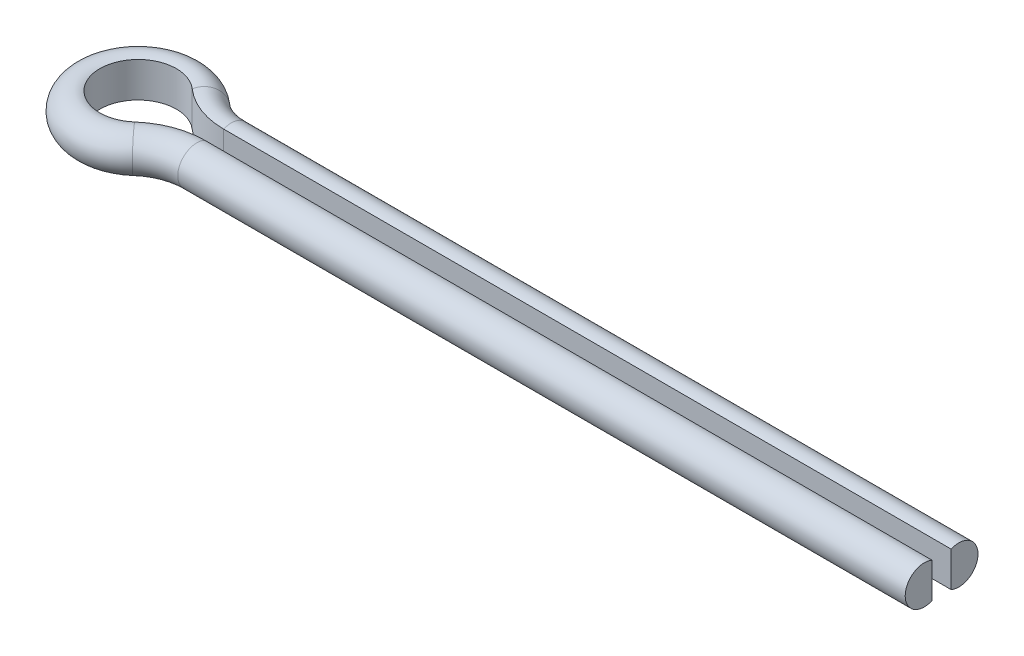
SolidWorks part; units mm, degrees
ref_plane "Front Plane" through (0, 0, 0) normal (0, 0, 1) x (1, 0, 0)
ref_plane "Top Plane" through (0, 0, 0) normal (0, 1, 0) x (1, 0, 0)
ref_plane "Right Plane" through (0, 0, 0) normal (1, 0, 0) x (0, 0, -1)
sketch "Sketch2" plane through (0, 0, 0) normal (0, 1, 0) x (1, 0, 0)
  line L0 (0, 0) -> (53.9373, 0) construction
  line L1 (104.8412, 1.25) -> (9.9216, 1.25)
  line L2 (104.8412, -1.25) -> (9.9216, -1.25)
  arc A0 (3.3072, 3.75) -> (3.3072, -3.75) centre (0, 0) ccw
  arc A1 (9.9216, -1.25) -> (3.3072, -3.75) centre (9.9216, -11.25) ccw
  arc A2 (9.9216, 1.25) -> (3.3072, 3.75) centre (9.9216, 11.25) cw
  point P9 (4.8412, -1.25)
  point P12 (4.8412, 1.25)
  dimension "D1" = 10
  dimension "D4" = 10
  dimension "D2" = 1.25
  dimension "D3" = 100
ref_plane "Plane1" through (104.8412, 0, 0) normal (-1, 0, 0) x (0, 0, 1)
sketch "Sketch3" plane through (104.8412, 0, 0) normal (-1, 0, 0) x (0, 0, 1)
  line L0 (1.25, 2.2913) -> (1.25, -2.2913)
  arc A0 (1.25, -2.2913) -> (1.25, 2.2913) centre (2.25, 0) ccw
  point P1 (0, 0)
  point P9 (1.25, 0)
  dimension "D1" = 5
  dimension "D2" = 1
sweep "Sweep1" add profiles "Sketch3" path "Sketch2"
